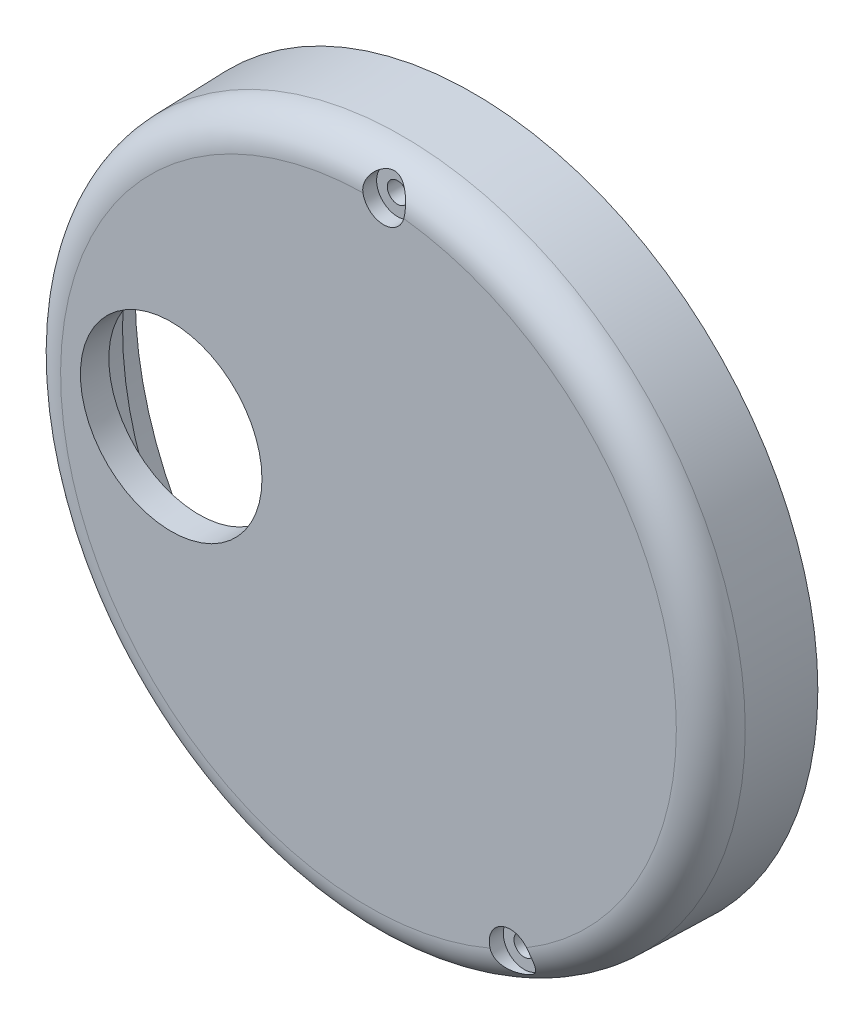
SolidWorks part; units mm, degrees
ref_plane "Front Plane" through (0, 0, 0) normal (0, 0, 1) x (1, 0, 0)
ref_plane "Top Plane" through (0, 0, 0) normal (0, 1, 0) x (1, 0, 0)
ref_plane "Right Plane" through (0, 0, 0) normal (1, 0, 0) x (0, 0, -1)
sketch "Sketch2" plane through (0, 0, -134.7955) normal (0, 0, 1) x (1, 0, 0)
  circle A3 centre (-8.948, 38.989) radius 49.1974
  dimension "D1" = 98.3948
  dimension "D2" = 40.0026
  dimension "D3" = 38.989
extrude "Boss-Extrude1" add sketch "Sketch2" along normal blind 9 draft 1.5 and the other way blind 6 draft 1.5
shell "Shell1" thickness 4
sketch "Sketch4" plane through (0, 0, -140.7955) normal (0, 0, -1) x (-1, 0, 0)
  circle A2 centre (8.948, 38.989) radius 47.1045
  circle A3 centre (8.948, 38.989) radius 47.1045
  dimension "D1" = 2.25
fillet "Fillet1" radius 5 1 edges at (40.0137, 38.989, -125.7955)
sketch "Sketch6" plane through (0, 0, -125.7955) normal (0, 0, 1) x (1, 0, 0)
  circle A0 centre (-37.2018, 40.3356) radius 13
extrude "wireHoles" cut sketch "Sketch6" against normal blind 10 draft 1
sketch "Sketch7" plane through (0, 0, -140.7955) normal (0, 0, -1) x (-1, 0, 0)
  circle A2 centre (8.948, 38.989) radius 48.4045
  circle A3 centre (8.948, 38.989) radius 48.4045
  dimension "D1" = 1.3
extrude "insideLayer" cut sketch "Sketch7" against normal blind 5 draft 1
sketch "Sketch8" plane through (0, 0, -125.7955) normal (0, 0, 1) x (1, 0, 0)
  circle A0 centre (11.3518, -0.7201) radius 1.5003
  circle A1 centre (-6.7874, 83.5813) radius 1.5016
  circle A2 centre (-8.948, 38.989) radius 44.091 construction
  dimension "D1" = 44.6446
  dimension "D3" = 86.2308
  dimension "D4" = 44.5923
  dimension "D5" = 39.7091
extrude "nail" cut sketch "Sketch8" against normal blind 10 draft 1
sketch "Sketch9" plane through (0, 0, -125.7955) normal (0, 0, 1) x (1, 0, 0)
  circle A0 centre (-6.7874, 83.5813) radius 3
  circle A1 centre (11.3518, -0.7201) radius 3
extrude "nailHead" cut sketch "Sketch9" against normal blind 2
